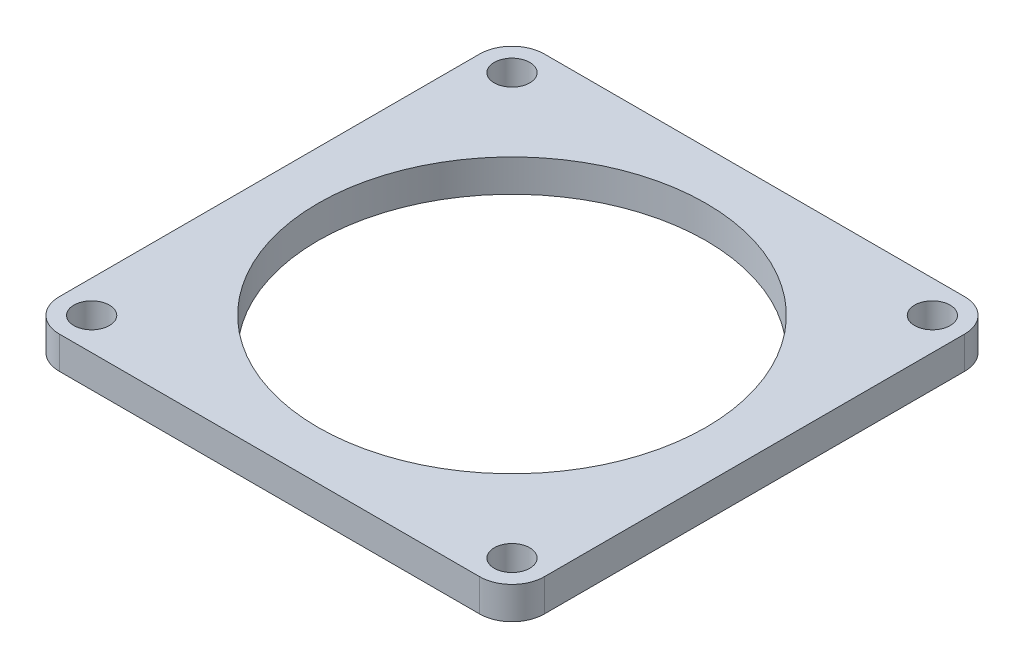
SolidWorks part; units mm, degrees
ref_plane "Front Plane" through (0, 0, 0) normal (0, 0, 1) x (1, 0, 0)
ref_plane "Top Plane" through (0, 0, 0) normal (0, 1, 0) x (1, 0, 0)
ref_plane "Right Plane" through (0, 0, 0) normal (1, 0, 0) x (0, 0, -1)
sketch "Sketch1" plane through (0, 0, 0) normal (0, 1, 0) x (1, 0, 0)
  line L1 (-38.1, -38.1) -> (38.1, -38.1)
  line L2 (-38.1, -38.1) -> (-38.1, 38.1)
  line L3 (-38.1, 38.1) -> (38.1, 38.1)
  line L4 (38.1, -38.1) -> (38.1, 38.1)
  line L5 (-38.1, -38.1) -> (38.1, 38.1) construction
  line L6 (-38.1, 38.1) -> (38.1, -38.1) construction
  circle A0 centre (33.02, 33.02) radius 2.794
  circle A1 centre (33.02, -33.02) radius 2.794
  circle A2 centre (-33.02, -33.02) radius 2.794
  circle A3 centre (-33.02, 33.02) radius 2.794
  circle A4 centre (0, 0) radius 30.48
  point P0 (0, 0)
  point P17 (0, 0)
  dimension "D3" = 5.588
  dimension "D4" = 5.08
  dimension "D6" = 60.96
  dimension "D1" = 76.2
  dimension "D2" = 76.2
  dimension "D5" = 4
extrude "Boss-Extrude1" add sketch "Sketch1" along normal blind 5.08
fillet "Fillet1" radius 5.08 4 edges at (-38.1, 2.54, -38.1) (-38.1, 2.54, 38.1) (38.1, 2.54, -38.1) (38.1, 2.54, 38.1)
